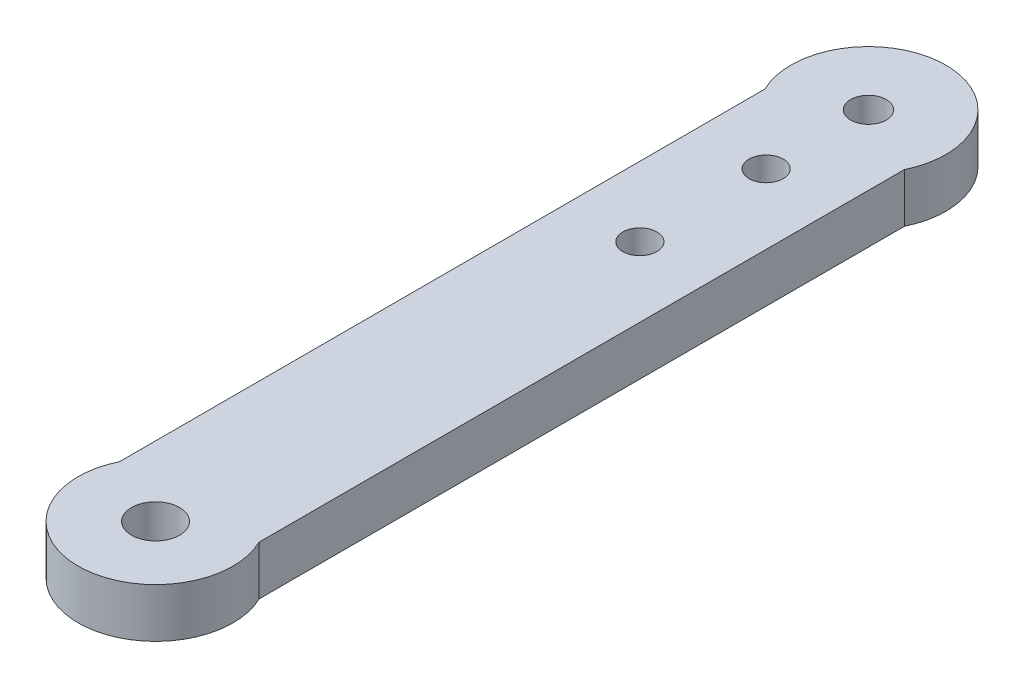
SolidWorks part; units mm, degrees
ref_plane "Front Plane" through (0, 0, 0) normal (0, 0, 1) x (1, 0, 0)
ref_plane "Top Plane" through (0, 0, 0) normal (0, 1, 0) x (1, 0, 0)
ref_plane "Right Plane" through (0, 0, 0) normal (1, 0, 0) x (0, 0, -1)
sketch "Sketch1" plane through (0, 0, 0) normal (0, 1, 0) x (1, 0, 0)
  line L1 (-4.5, -43.8206) -> (-4.5, -2.1794)
  line L4 (4.5, -43.8206) -> (4.5, -2.1794)
  line L5 (-4.5, -2.1794) -> (0, 0) construction
  line L6 (0, 0) -> (4.5, -2.1794) construction
  line L7 (-4.5, -2.1794) -> (4.5, -2.1794) construction
  arc A1 (4.5, -2.1794) -> (-4.5, -2.1794) centre (0, 0) ccw
  arc A2 (-4.5, -43.8206) -> (4.5, -43.8206) centre (0, -46) ccw
  circle A3 centre (0, -46) radius 1.55
  circle A5 centre (0, -6.6) radius 1.1
  circle A6 centre (0, -14.75) radius 1.1
  circle A25 centre (0, 0) radius 1.15
  dimension "D2" = 2.2
  dimension "D3" = 10
  dimension "D6" = 10
  dimension "D5" = 3.1
  dimension "D8" = 2.3
  dimension "D1" = 8.15
  dimension "D4" = 9
  dimension "D7" = 46
  dimension "D9" = 6.6
extrude "Boss-Extrude1" add sketch "Sketch1" along normal blind 3.175
